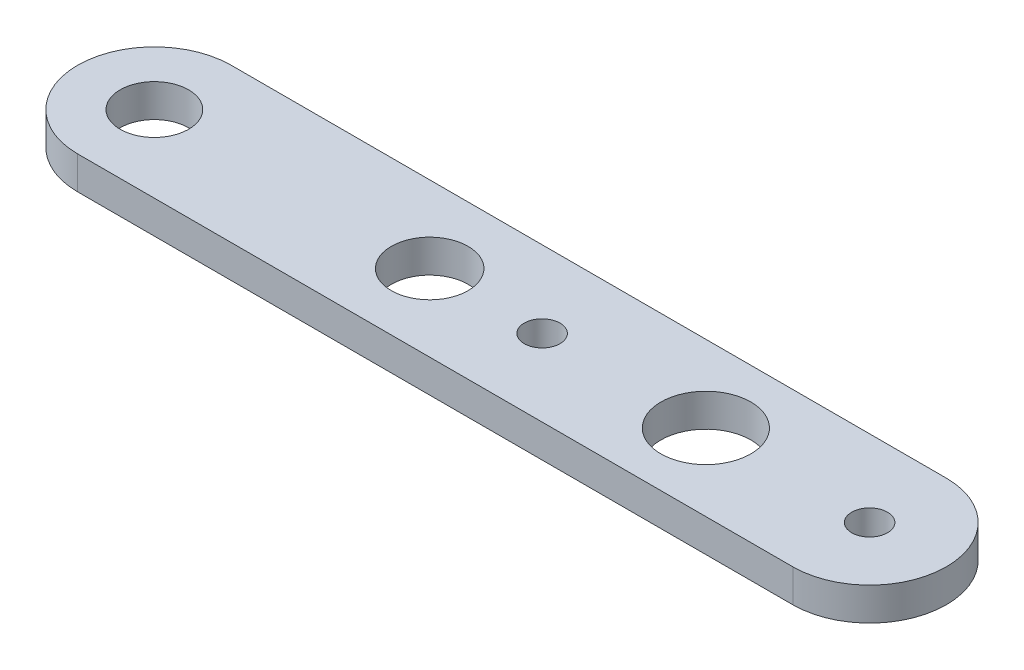
SolidWorks part; units mm, degrees
ref_plane "Front Plane" through (0, 0, 0) normal (0, 0, 1) x (1, 0, 0)
ref_plane "Top Plane" through (0, 0, 0) normal (0, 1, 0) x (1, 0, 0)
ref_plane "Right Plane" through (0, 0, 0) normal (1, 0, 0) x (0, 0, -1)
sketch "Sketch1" plane through (0, 0, 0) normal (0, 1, 0) x (1, 0, 0)
  line L0 (0, 0) -> (82.8167, 0) construction
  line L1 (0, 8.89) -> (82.8167, 8.89)
  line L2 (0, -8.89) -> (82.8167, -8.89)
  line L3 (44.8945, 0) -> (82.8167, 0) construction
  arc A0 (0, 8.89) -> (0, -8.89) centre (0, 0) ccw
  arc A1 (82.8167, -8.89) -> (82.8167, 8.89) centre (82.8167, 0) ccw
  circle A2 centre (0, 0) radius 3.9624
  circle A3 centre (82.8167, 0) radius 2.0701
  circle A4 centre (44.8945, 0) radius 2.0701
  circle A5 centre (63.8556, 0) radius 5.207
  circle A6 centre (31.877, 0) radius 4.445
  point P3 (41.4084, 0)
  dimension "D1" = 8.89
  dimension "D3" = 7.9248
  dimension "D5" = 4.1402
  dimension "D6" = 10.414
  dimension "D8" = 8.89
  dimension "D4" = 37.9222
  dimension "D2" = 63.8556
  dimension "D7" = 31.877
extrude "Boss-Extrude1" add sketch "Sketch1" along normal blind 3.81
equation "\"D4@Sketch1\"=1.32+0.173"
equation "\"D2@Sketch1\"=2.233+1/2*0.25+1/2*0.312"
equation "\"D7@Sketch1\"=1.005+1/2*0.312+1/2*0.188"
